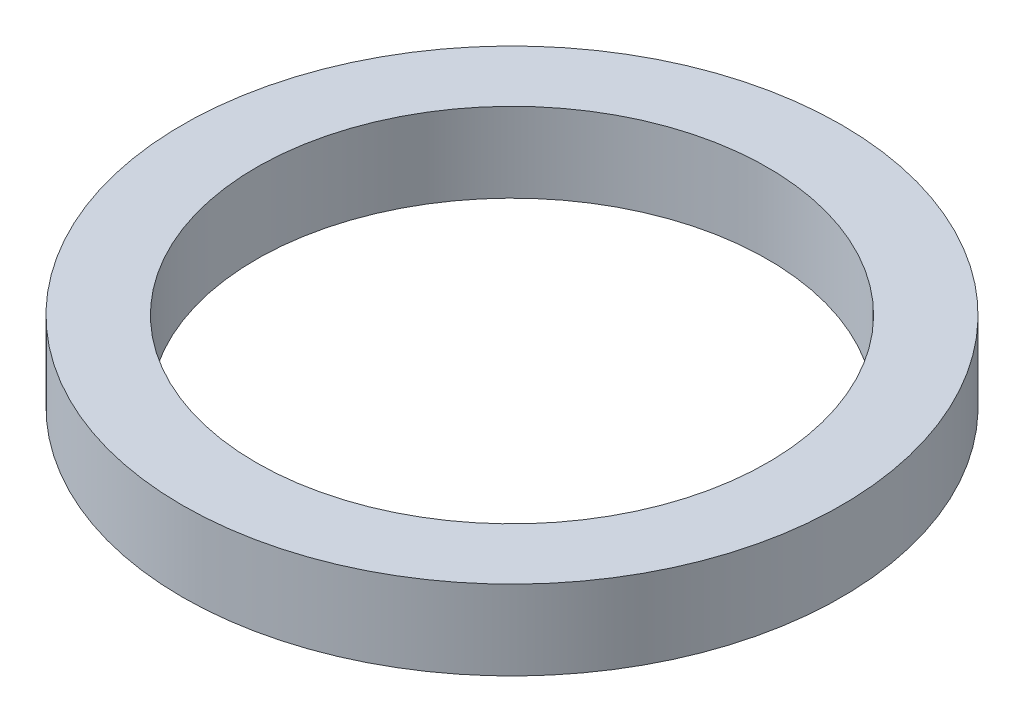
SolidWorks part; units mm, degrees
material "不锈钢 (铁素体)"
ref_plane "前视基准面" through (0, 0, 0) normal (0, 0, 1) x (1, 0, 0)
ref_plane "上视基准面" through (0, 0, 0) normal (0, 1, 0) x (1, 0, 0)
ref_plane "右视基准面" through (0, 0, 0) normal (1, 0, 0) x (0, 0, -1)
sketch "草图1" plane through (0, 0, 0) normal (0, 1, 0) x (1, 0, 0)
  circle A0 centre (0, 0) radius 22.5
  circle A1 centre (0, 0) radius 29
  dimension "D1" = 45
  dimension "D2" = 58
extrude "凸台-拉伸1" add sketch "草图1" along normal blind 7
